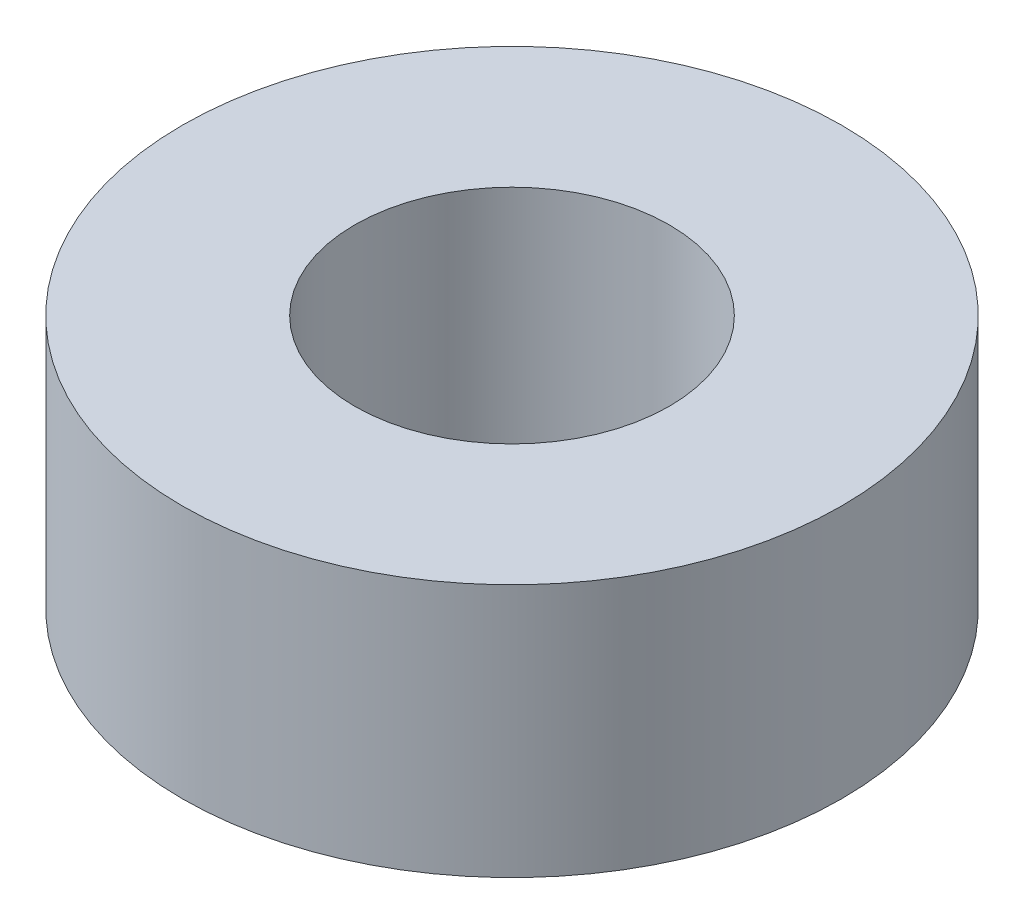
SolidWorks part; units mm, degrees
ref_plane "Front" through (0, 0, 0) normal (0, 0, 1) x (1, 0, 0)
ref_plane "Top" through (0, 0, 0) normal (0, 1, 0) x (1, 0, 0)
ref_plane "Right" through (0, 0, 0) normal (1, 0, 0) x (0, 0, -1)
sketch "Sketch1" plane through (0, 0, 0) normal (0, 1, 0) x (1, 0, 0)
  circle A0 centre (0, 0) radius 6.2
  circle A1 centre (0, 0) radius 13
extrude "Boss-Extrude1" add sketch "Sketch1" along normal blind 10
